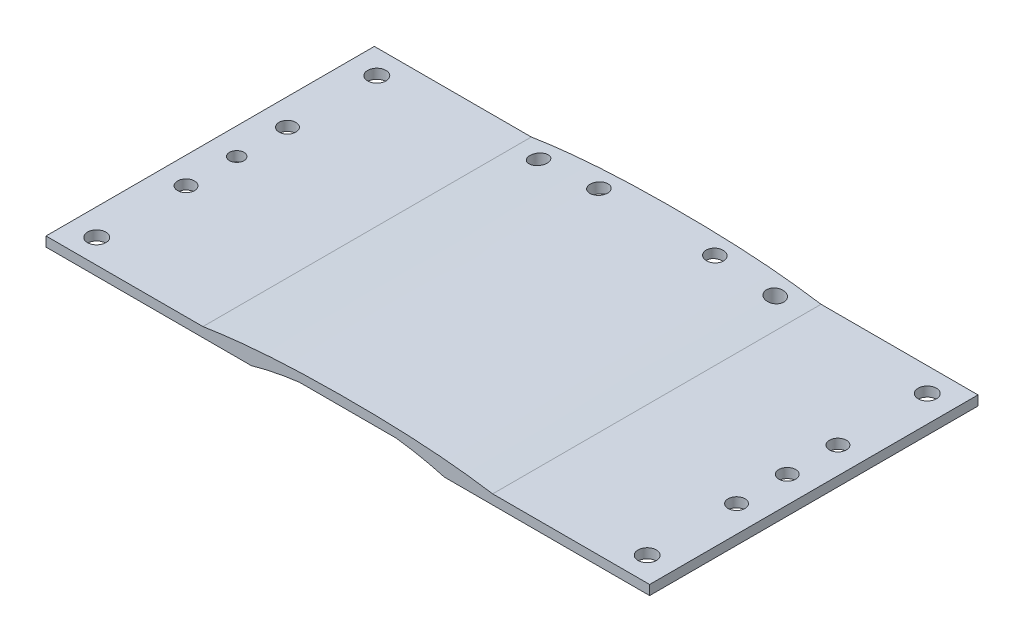
SolidWorks part; units mm, degrees
ref_plane "前视基准面" through (0, 0, 0) normal (0, 0, 1) x (1, 0, 0)
ref_plane "上视基准面" through (0, 0, 0) normal (0, 1, 0) x (1, 0, 0)
ref_plane "右视基准面" through (0, 0, 0) normal (1, 0, 0) x (0, 0, -1)
other "Configuration Table"
sketch "草图1" plane through (0, 0, 0) normal (0, 1, 0) x (1, 0, 0)
  line L0 (0, 0) -> (-57, 0) construction
  line L1 (-57, 0) -> (57, 0) construction
  line L2 (-57, 0) -> (-57, 10.5) construction
  line L3 (-57, 10.5) -> (-57, 0) construction
  line L4 (-57, 0) -> (-57, -10.5) construction
  line L5 (-57, 0) -> (-57, 29) construction
  line L6 (-57, 29) -> (-57, 0) construction
  line L7 (-57, 0) -> (-57, -29) construction
  line L8 (57, 0) -> (57, 10.5) construction
  line L9 (57, 10.5) -> (57, -10.5) construction
  line L10 (57, -10.5) -> (57, 0) construction
  line L11 (57, 0) -> (57, 29) construction
  line L12 (57, 29) -> (57, 0) construction
  line L13 (57, 0) -> (57, -29) construction
  line L15 (-62.5, 34) -> (62.5, 34)
  line L16 (-62.5, 34) -> (-62.5, -34)
  line L17 (-62.5, -34) -> (62.5, -34)
  line L18 (62.5, 34) -> (62.5, -34)
  line L19 (-62.5, 34) -> (62.5, -34) construction
  line L20 (-62.5, -34) -> (62.5, 34) construction
  circle A0 centre (-57, 0) radius 1.5
  circle A1 centre (57, 0) radius 1.75
  circle A2 centre (57, -29) radius 1.9
  circle A3 centre (57, 29) radius 1.9
  circle A4 centre (57, 10.5) radius 1.75
  circle A5 centre (57, -10.5) radius 1.75
  circle A6 centre (-57, 10.5) radius 1.75
  circle A7 centre (-57, -10.5) radius 1.75
  circle A8 centre (-57, 29) radius 1.9
  circle A9 centre (-57, -29) radius 1.9
  dimension "D3" = 3
  dimension "D4" = 3.5
  dimension "D13" = 3.8
  dimension "D14" = 3.8
  dimension "D15" = 3.5
  dimension "D16" = 3.5
  dimension "D17" = 3.5
  dimension "D18" = 3.5
  dimension "D19" = 3.8
  dimension "D20" = 3.8
  dimension "D1" = 57
  dimension "D2" = 114
  dimension "D5" = 10.5
  dimension "D6" = 10.5
  dimension "D7" = 29
  dimension "D8" = 29
  dimension "D9" = 10.5
  dimension "D10" = 21
  dimension "D11" = 29
  dimension "D12" = 29
  dimension "D21" = 68
  dimension "D22" = 125
extrude "凸台-拉伸1" add sketch "草图1" along normal blind 2
sketch "草图3" plane through (0, 0, 34) normal (0, 0, 1) x (1, 0, 0)
  line L0 (0, 2) -> (-20, 2) construction
  line L1 (-62.5, 2) -> (62.5, 2) construction
  line L2 (-20, 2) -> (20, 2) construction
  line L3 (0, 2) -> (0, 4) construction
  line L4 (0, 0) -> (30, 0) construction
  line L5 (-62.5, 0) -> (62.5, 0) construction
  line L6 (30, 0) -> (-30, 0) construction
  line L7 (-30, 0) -> (-30, 2) construction
  line L8 (30, 0) -> (30, 2) construction
  line L9 (-30, 0) -> (-40, 0) construction
  line L10 (30, 0) -> (40, 0) construction
  line L11 (-40, 0) -> (40, 0)
  spline S0 degree 3 poles (-40, 0) (-26.9311, 3.2105) (0, 4.7895) (26.9311, 3.2105) (40, 0) knots 0 0 0 0 0.5 1 1 1 1
  dimension "D1" = 20
  dimension "D2" = 40
  dimension "D3" = 2
  dimension "D4" = 30
  dimension "D5" = 60
  dimension "D6" = 10
  dimension "D7" = 10
extrude "凸台-拉伸2" add sketch "草图3" against normal up to surface (68 mm away) up to face at (0, 1, -34)
sketch "草图4" plane through (0, 0, 34) normal (0, 0, 1) x (1, 0, 0)
  line L0 (-10, 0) -> (-20, 0) construction
  line L1 (-10, 2) -> (10, 2)
  line L2 (-10, 2) -> (-10, -2)
  line L3 (-10, -2) -> (10, -2)
  line L4 (10, 2) -> (10, -2)
  line L5 (-10, 2) -> (10, -2) construction
  line L6 (-10, -2) -> (10, 2) construction
  line L7 (-62.5, 0) -> (62.5, 0) construction
  line L8 (10, 0) -> (20, 0) construction
  line L9 (15, 0) -> (15, 1.2) construction
  line L10 (15, 1.2) -> (-15, 1.2) construction
  line L11 (20, 0) -> (10, 0)
  line L12 (10, 0) -> (10, 2)
  line L13 (-10, 2) -> (-10, 0)
  line L14 (-10, 0) -> (-20, 0)
  spline S0 degree 2 poles (-20, 0) (-15.0768, 1.3847) (-10, 2) knots 0 0 0 1 1 1
  spline S1 degree 2 poles (10, 2) (15.0768, 1.3847) (20, 0) knots 0 0 0 1 1 1
  point P0 (0, 0)
  line M9 (-62.5, 0) -> (62.5, 0)
  dimension "D1" = 4
  dimension "D2" = 20
  dimension "D3" = 10
  dimension "D4" = 10
  dimension "D5" = 1.2
  dimension "D6" = 30
extrude "切除-拉伸1" cut sketch "草图4" against normal up to surface (68 mm away) contours L4 L1 L2 M9 | S0 L2 M9 | S1 L4 M9 up to face at (-5, 1.3333, -34)
sketch "草图5" plane through (0, 0, 0) normal (0, 1, 0) x (1, 0, 0)
  line L0 (0, 0) -> (0, 34) construction
  line L1 (10, 34) -> (-10, 34) construction
  line L2 (0, 34) -> (0, 30) construction
  line L3 (0, 30) -> (-12, 30) construction
  line L4 (-12, 30) -> (12, 30) construction
  line L5 (12, 30) -> (24.5, 30) construction
  line L6 (24.5, 30) -> (-12, 30) construction
  line L7 (-12, 30) -> (-24.5, 30) construction
  circle A0 centre (-24.5, 30) radius 1.8
  circle A1 centre (-12, 30) radius 1.8
  circle A2 centre (12, 30) radius 1.8
  circle A3 centre (24.5, 30) radius 1.8
  dimension "D6" = 3.6
  dimension "D7" = 3.6
  dimension "D8" = 3.6
  dimension "D9" = 3.6
  dimension "D1" = 4
  dimension "D2" = 12
  dimension "D3" = 24
  dimension "D4" = 12.5
  dimension "D5" = 12.5
extrude "切除-拉伸2" cut sketch "草图5" along normal blind 10
